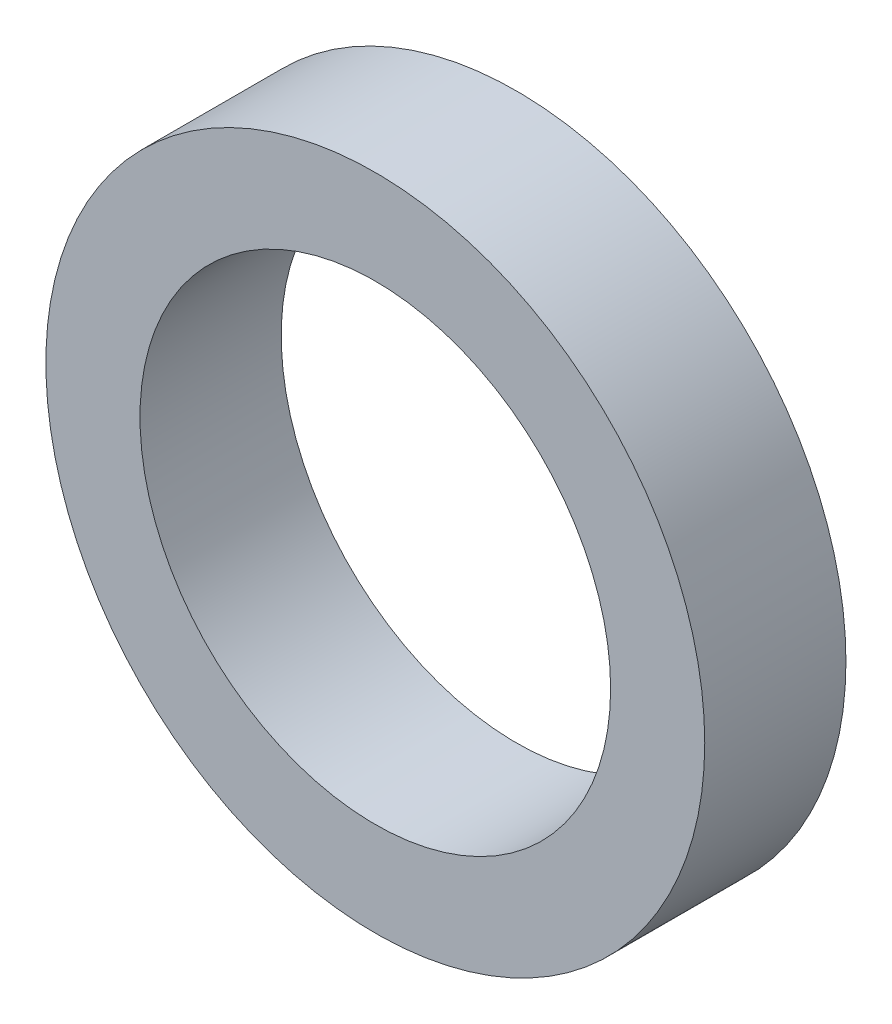
SolidWorks part; units mm, degrees
material "Laiton"
ref_plane "Plan de face" through (0, 0, 0) normal (0, 0, 1) x (1, 0, 0)
ref_plane "Plan de dessus" through (0, 0, 0) normal (0, 1, 0) x (1, 0, 0)
ref_plane "Plan de droite" through (0, 0, 0) normal (1, 0, 0) x (0, 0, -1)
sketch "Esquisse1" plane through (0, 0, 0) normal (0, 0, 1) x (1, 0, 0)
  circle A0 centre (0, 0) radius 1.5
  circle A1 centre (0, 0) radius 2.1
  dimension "D1" = 4.2
  dimension "D2" = 3
extrude "Extrusion1" add sketch "Esquisse1" along normal blind 0.9
